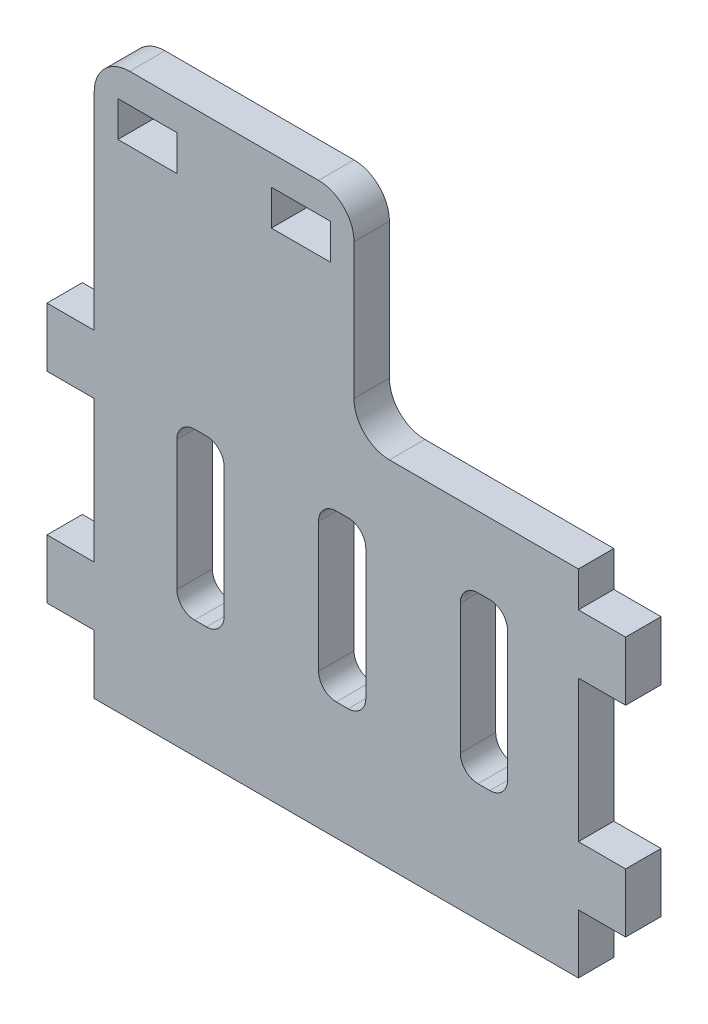
SolidWorks part; units mm, degrees
ref_plane "Front Plane" through (0, 0, 0) normal (0, 0, 1) x (1, 0, 0)
ref_plane "Top Plane" through (0, 0, 0) normal (0, 1, 0) x (1, 0, 0)
ref_plane "Right Plane" through (0, 0, 0) normal (1, 0, 0) x (0, 0, -1)
sketch "草图1" plane through (0, 0, 0) normal (0, 0, 1) x (1, 0, 0)
  line L1 (-20.5, -15) -> (20.5, -15)
  line L2 (-20.5, -15) -> (-20.5, 15)
  line L3 (-20.5, 15) -> (20.5, 15)
  line L4 (20.5, -15) -> (20.5, 15)
  line L5 (-20.5, -15) -> (20.5, 15) construction
  line L6 (-20.5, 15) -> (20.5, -15) construction
  point P0 (0, 0)
  dimension "41" = 41
  dimension "D2" = 30
extrude "凸台-拉伸1" add sketch "草图1" along normal blind 3
sketch "草图2" plane through (0, 0, 3) normal (0, 0, 1) x (1, 0, 0)
  line L0 (0, 15) -> (0, -17.8549) construction
  line L1 (20.5, 15) -> (-20.5, 15) construction
  line L2 (20.5, -15) -> (20.5, 15) construction
  line L3 (20.5, -10) -> (24.5, -10)
  line L4 (20.5, -10) -> (20.5, -5)
  line L5 (20.5, -5) -> (24.5, -5)
  line L6 (24.5, -10) -> (24.5, -5)
  line L7 (20.5, -10) -> (24.5, -5) construction
  line L8 (20.5, -5) -> (24.5, -10) construction
  line L9 (-20.5, -15) -> (20.5, -15) construction
  line L10 (20.5, 12) -> (24.5, 12)
  line L11 (20.5, 12) -> (20.5, 7)
  line L12 (20.5, 7) -> (24.5, 7)
  line L13 (24.5, 12) -> (24.5, 7)
  line L14 (20.5, 12) -> (24.5, 7) construction
  line L15 (20.5, 7) -> (24.5, 12) construction
  line L16 (-20.5, -5) -> (-24.5, -5)
  line L17 (-24.5, -10) -> (-24.5, -5)
  line L18 (-20.5, -10) -> (-24.5, -10)
  line L19 (-20.5, -10) -> (-20.5, -5)
  line L20 (-20.5, 7) -> (-24.5, 7)
  line L21 (-24.5, 12) -> (-24.5, 7)
  line L22 (-20.5, 12) -> (-24.5, 12)
  line L23 (-20.5, 12) -> (-20.5, 7)
  point P9 (22.5, -7.5)
  point P16 (22.5, 9.5)
  dimension "D1" = 4
  dimension "D2" = 5
  dimension "D3" = 4
  dimension "D4" = 5
  dimension "D5" = 12
  dimension "D6" = 5
extrude "凸台-拉伸2" add sketch "草图2" against normal up to surface (3 mm away) up to face at (0, 0, 0)
sketch "草图3" plane through (0, 0, 3) normal (0, 0, 1) x (1, 0, 0)
  line L1 (-20.5, 15) -> (1.5, 15)
  line L2 (-20.5, 15) -> (-20.5, 32.5)
  line L3 (-20.5, 32.5) -> (1.5, 32.5)
  line L4 (1.5, 15) -> (1.5, 32.5)
  line L5 (-20.5, 15) -> (1.5, 32.5) construction
  line L6 (-20.5, 32.5) -> (1.5, 15) construction
  point P4 (-9.5, 23.75)
  dimension "D1" = 17.5
  dimension "D2" = 22
extrude "凸台-拉伸3" add sketch "草图3" against normal up to surface (3 mm away) up to face at (0, 0.8, 0)
sketch "草图4" plane through (0, 0, 3) normal (0, 0, 1) x (1, 0, 0)
  line L0 (-20.5, 30) -> (1.5, 30) construction
  line L1 (-20.5, 32.5) -> (-20.5, 12) construction
  line L2 (1.5, 15) -> (1.5, 32.5) construction
  line L3 (1.5, 32.5) -> (-20.5, 32.5) construction
  line L5 (-18.5, 30) -> (-13.5, 30)
  line L6 (-18.5, 30) -> (-18.5, 27)
  line L7 (-18.5, 27) -> (-13.5, 27)
  line L8 (-13.5, 30) -> (-13.5, 27)
  line L9 (-18.5, 30) -> (-13.5, 27) construction
  line L10 (-18.5, 27) -> (-13.5, 30) construction
  line L11 (-5.5, 30) -> (-0.5, 30)
  line L12 (-5.5, 30) -> (-5.5, 27)
  line L13 (-5.5, 27) -> (-0.5, 27)
  line L14 (-0.5, 30) -> (-0.5, 27)
  line L15 (-5.5, 30) -> (-0.5, 27) construction
  line L16 (-5.5, 27) -> (-0.5, 30) construction
  point P12 (-16, 28.5)
  point P17 (-3, 28.5)
  dimension "D1" = 2.5
  dimension "D2" = 3
  dimension "D3" = 2
  dimension "D4" = 5
  dimension "D5" = 2
  dimension "D6" = 5
  dimension "D7" = 3
extrude "切除-拉伸1" cut sketch "草图4" against normal blind 10
fillet "圆角1" radius 3 3 edges at (-20.5, 32.5, 1.5) (1.5, 32.5, 1.5) (1.5, 15, 1.5)
sketch "草图5" plane through (0, 0, 3) normal (0, 0, 1) x (1, 0, 0)
  line L0 (-20.5, -15) -> (20.5, -15) construction
  line L1 (-13.5, 9) -> (-9.5, 9)
  line L2 (-13.5, 9) -> (-13.5, -5)
  line L3 (-13.5, -5) -> (-9.5, -5)
  line L4 (-9.5, 9) -> (-9.5, -5)
  line L5 (-13.5, 9) -> (-9.5, -5) construction
  line L6 (-13.5, -5) -> (-9.5, 9) construction
  line L7 (-20.5, 7) -> (-20.5, -5) construction
  line L8 (-1.5, 9) -> (-1.5, -5)
  line L9 (-1.5, 9) -> (2.5, 9)
  line L10 (2.5, 9) -> (2.5, -5)
  line L11 (-1.5, -5) -> (2.5, -5)
  line L12 (10.5, 9) -> (10.5, -5)
  line L13 (10.5, 9) -> (14.5, 9)
  line L14 (14.5, 9) -> (14.5, -5)
  line L15 (10.5, -5) -> (14.5, -5)
  point P4 (-11.5, 2)
  dimension "D1" = 14
  dimension "D2" = 4
  dimension "10" = 10
  dimension "D4" = 7
  dimension "D5" = 3
extrude "切除-拉伸2" cut sketch "草图5" against normal blind 10
fillet "圆角2" radius 1.5 12 edges at (10.5, 9, 1.5) (14.5, 9, 1.5) (14.5, -5, 1.5) (10.5, -5, 1.5) (2.5, 9, 1.5) (-1.5, 9, 1.5) (2.5, -5, 1.5) (-1.5, -5, 1.5) (-9.5, 9, 1.5) (-13.5, 9, 1.5) (-13.5, -5, 1.5) (-9.5, -5, 1.5)
